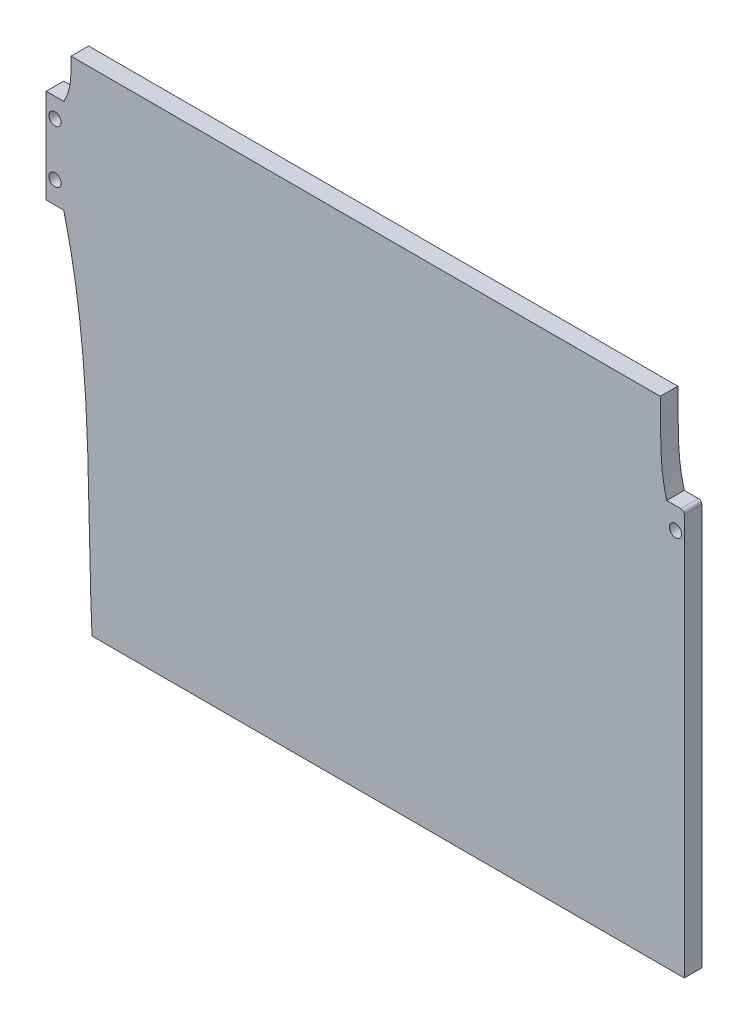
SolidWorks part; units mm, degrees
ref_plane "Front Plane" through (0, 0, 0) normal (0, 0, 1) x (1, 0, 0)
ref_plane "Top Plane" through (0, 0, 0) normal (0, 1, 0) x (1, 0, 0)
ref_plane "Right Plane" through (0, 0, 0) normal (1, 0, 0) x (0, 0, -1)
sketch "Sketch1" plane through (0, 0, 0) normal (0, 0, 1) x (1, 0, 0)
  line L16 (-91.6662, -176.9297) -> (8.3338, -176.9297) construction
  line L25 (-93.75, -249.1471) -> (-98.75, -249.1471)
  line L26 (-98.75, -249.1471) -> (-98.75, -275.9636)
  line L27 (-98.75, -275.9636) -> (-93.75, -275.9636)
  line L29 (81.9, -261.7137) -> (77.9, -261.7137)
  line L32 (82.9, -274.0355) -> (82.9, -262.7137)
  line L33 (-77.0223, -236.458) -> (-70.2338, -236.458) construction
  line L34 (-91.6662, -236.958) -> (76.0558, -236.958)
  line L35 (-85.6961, -376.9297) -> (82.9, -376.9297)
  circle A0 centre (-96.2494, -269.714) radius 1.75
  circle A1 centre (-96.2437, -254.714) radius 1.75
  circle A2 centre (80.4, -267.8746) radius 1.75
  arc A4 (81.9, -261.7137) -> (82.9, -262.7137) centre (81.9, -262.7137) cw
  spline S0 degree 3 poles (-93.75, -249.1471) (-91.5427, -245.5167) (-91.5817, -241.057) (-91.6662, -236.958) knots 0 0 0 0 1 1 1 1
  spline S1 degree 3 poles (77.9, -261.7137) (75.5882, -253.5989) (76.3402, -245.2397) (76.0558, -236.958) knots 0 0 0 0 1 1 1 1
  spline S2 degree 3 poles (-93.75, -275.9636) (-85.3288, -309.0235) (-87.2427, -343.1648) (-85.6961, -376.9297) knots 0 0 0 0 1 1 1 1
  spline S3 degree 3 poles (82.9, -274.0355) (82.9, -308.3336) (82.9, -342.6316) (82.9, -376.9297) knots 0 0 0 0 1 1 1 1
  point P26 (0, 0)
  point P30 (0, 0)
  point P31 (0, 0)
  dimension "D4" = 3.5
  dimension "D5" = 3.5
  dimension "D6" = 15
  dimension "D7" = 3.5
  dimension "D8" = 1
  dimension "D2" = 0.5
  dimension "D3" = 200
extrude "Boss-Extrude1" add sketch "Sketch1" along normal blind 5
